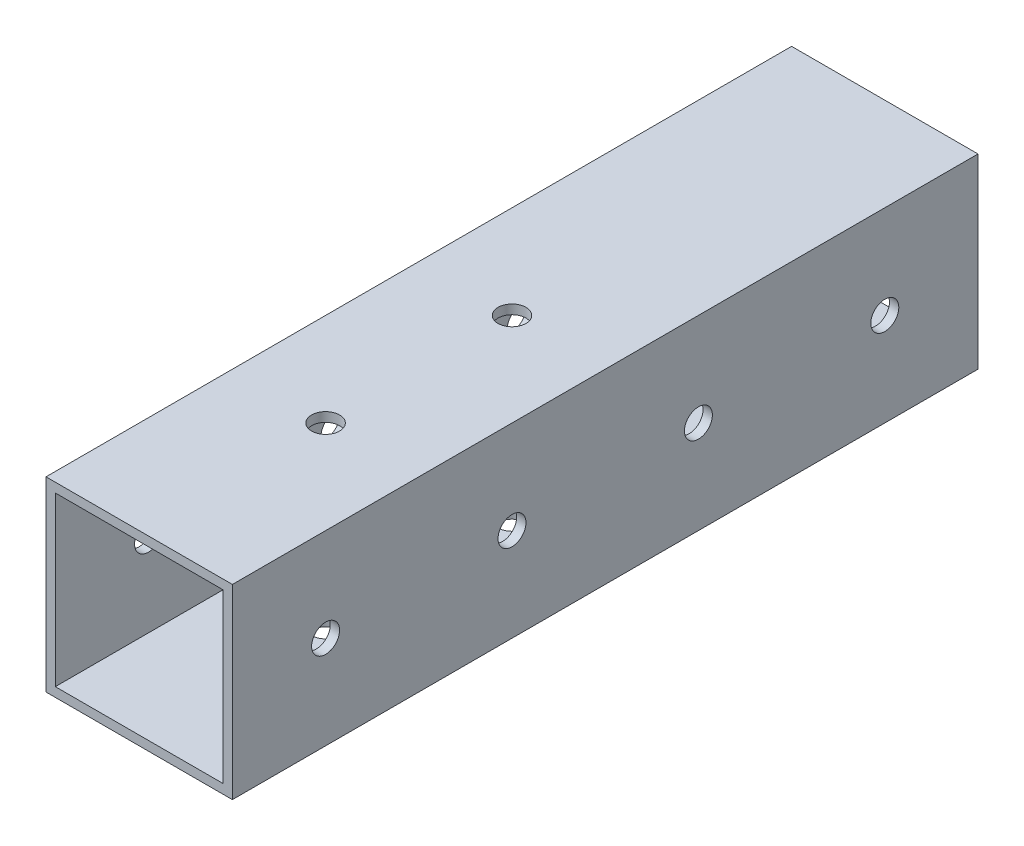
SolidWorks part; units mm, degrees
ref_plane "前视基准面" through (0, 0, 0) normal (0, 0, 1) x (1, 0, 0)
ref_plane "上视基准面" through (0, 0, 0) normal (0, 1, 0) x (1, 0, 0)
ref_plane "右视基准面" through (0, 0, 0) normal (1, 0, 0) x (0, 0, -1)
sketch "草图1" plane through (0, 0, 0) normal (0, 0, 1) x (1, 0, 0)
  line L1 (-10, 10) -> (10, 10)
  line L2 (-10, 10) -> (-10, -10)
  line L3 (-10, -10) -> (10, -10)
  line L4 (10, 10) -> (10, -10)
  line L5 (0, -10) -> (0, 10) construction
  line L6 (-10, 0) -> (10, 0) construction
  line L7 (-9, 9) -> (9, 9)
  line L8 (-9, 9) -> (-9, -9)
  line L9 (-9, -9) -> (9, -9)
  line L10 (9, 9) -> (9, -9)
  line L11 (0, -9) -> (0, 9) construction
  line L12 (-9, 0) -> (9, 0) construction
  point P0 (0, 0)
  point P4 (0, 0)
  dimension "D1" = 20
  dimension "D2" = 20
  dimension "D3" = 18
  dimension "D4" = 18
extrude "凸台-拉伸1" add sketch "草图1" along normal mid plane 80
sketch "草图2" plane through (0, 10, 0) normal (0, 1, 0) x (1, 0, 0)
  line L0 (0, 0) -> (0, -40) construction
  line L1 (10, -40) -> (-10, -40) construction
  line L3 (10, 40) -> (-10, 40) construction
  circle A0 centre (0, -20) radius 1.5
  circle A1 centre (0, 0) radius 1.5
  dimension "D1" = 3
  dimension "D3" = 3
  dimension "D2" = 20
  dimension "D4" = 40
extrude "切除-拉伸1" cut sketch "草图2" against normal blind 200
sketch "草图3" plane through (-10, 0, 0) normal (-1, 0, 0) x (0, 0, 1)
  line L0 (0, 0) -> (40, 0) construction
  line L1 (40, 10) -> (40, -10) construction
  line L2 (-40, 10) -> (-40, -10) construction
  line L3 (-40, 0) -> (-30, 0) construction
  circle A0 centre (10, 0) radius 1.5
  circle A1 centre (-10, 0) radius 1.5
  circle A2 centre (30, 0) radius 1.5
  circle A3 centre (-30, 0) radius 1.5
  dimension "D1" = 3
  dimension "D3" = 3
  dimension "D5" = 3
  dimension "D7" = 3
  dimension "D2" = 50
  dimension "D4" = 50
  dimension "D6" = 10
  dimension "D8" = 10
extrude "切除-拉伸2" cut sketch "草图3" against normal blind 40
